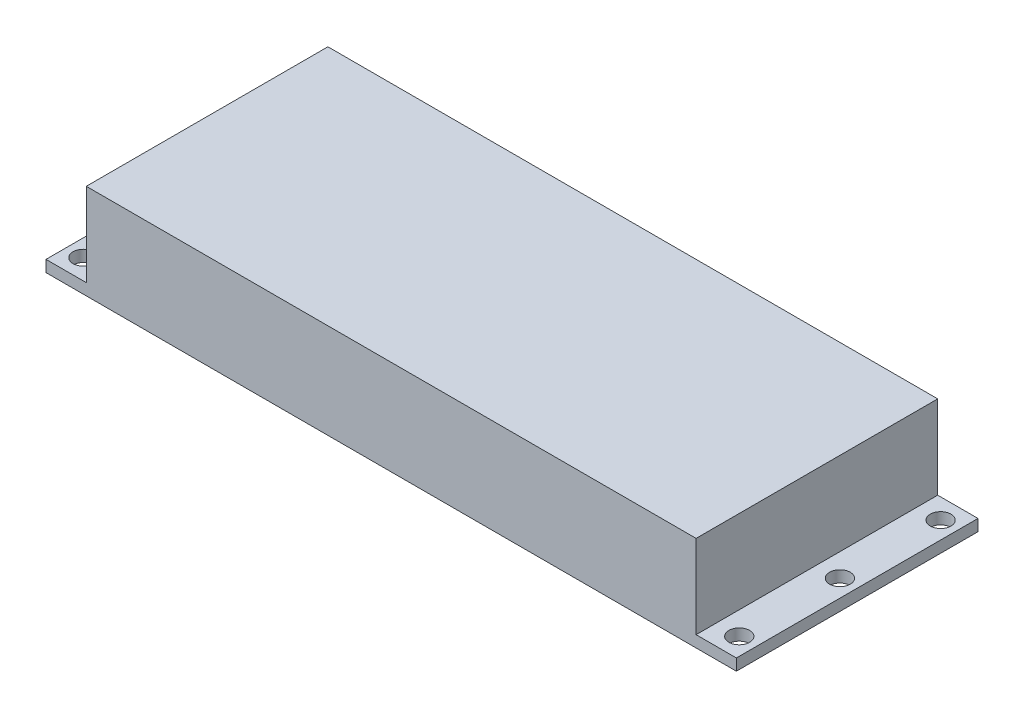
SolidWorks part; units mm, degrees
material "7075-T6 (SN)"
ref_plane "正面" through (0, 0, 0) normal (0, 0, 1) x (1, 0, 0)
ref_plane "平面" through (0, 0, 0) normal (0, 1, 0) x (1, 0, 0)
ref_plane "右側面" through (0, 0, 0) normal (1, 0, 0) x (0, 0, -1)
sketch "ｽｹｯﾁ1" plane through (0, 0, 0) normal (0, 1, 0) x (1, 0, 0)
  line L1 (-60, 21) -> (60, 21)
  line L2 (-60, 21) -> (-60, -21)
  line L3 (-60, -21) -> (60, -21)
  line L4 (60, 21) -> (60, -21)
  line L5 (-60, 21) -> (60, -21) construction
  line L6 (-60, -21) -> (60, 21) construction
  point P0 (0, 0)
  dimension "D1" = 120
  dimension "D2" = 42
extrude "ﾎﾞｽ - 押し出し1" add sketch "ｽｹｯﾁ1" along normal blind 2
sketch "ｽｹｯﾁ2" plane through (0, 2, 0) normal (0, 1, 0) x (1, 0, 0)
  line L0 (-60, -21) -> (60, -21) construction
  line L1 (-53, 21) -> (53, 21)
  line L2 (-53, 21) -> (-53, -21)
  line L3 (-53, -21) -> (53, -21)
  line L4 (53, 21) -> (53, -21)
  line L5 (-53, 21) -> (53, -21) construction
  line L6 (-53, -21) -> (53, 21) construction
  point P0 (0, 0)
  dimension "D1" = 106
extrude "ﾎﾞｽ - 押し出し2" add sketch "ｽｹｯﾁ2" along normal blind 14.5
sketch "ｽｹｯﾁ3" plane through (0, 2, 0) normal (0, 1, 0) x (1, 0, 0)
  line L0 (-60, 21) -> (-60, -21) construction
  line L2 (-53, 21) -> (-60, 21) construction
  circle A0 centre (-57, 17.5) radius 1.45
  circle A1 centre (-57, 0) radius 1.45
  dimension "D5" = 2.9
  dimension "D6" = 2.9
  dimension "D1" = 3
  dimension "D2" = 3.5
  dimension "D3" = 0
  dimension "D4" = 17.5
hole_wizard "M3 すきま穴1" positions "ｽｹｯﾁ5" profile "ｽｹｯﾁ4" hole size "M3" standard "JIS"
sketch "ｽｹｯﾁ5" plane through (0, 2, 0) normal (0, 1, 0) x (1, 0, 0)
  point P0 (-57, 17.5)
  point P3 (-57, 0)
sketch "ｽｹｯﾁ4" plane through (-57, 2, -17.5) normal (1, 0, 0) x (0, 0, 1)
  line L0 (0, 0) -> (0, 6.0815)
  line L1 (0, 6.0815) -> (1.8, 5)
  line L2 (1.8, 5) -> (1.8, 0)
  line L5 (1.8, 0) -> (0, 0)
  line L10 (0, 6.0815) -> (-1.8, 5) construction
  line L11 (0, -6.35) -> (0, 107.95) construction
  dimension "穴の直径" = 3.6
  dimension "穴の深さ" = 5
  dimension "ﾄﾞﾘﾙ角度" = 118
mirror "ﾐﾗｰ1" about plane through (0, 0, 0) normal (0, 0, 1) of "M3 すきま穴1"
mirror "ﾐﾗｰ2" about plane through (0, 0, 0) normal (1, 0, 0) of "ﾐﾗｰ1", "M3 すきま穴1"
